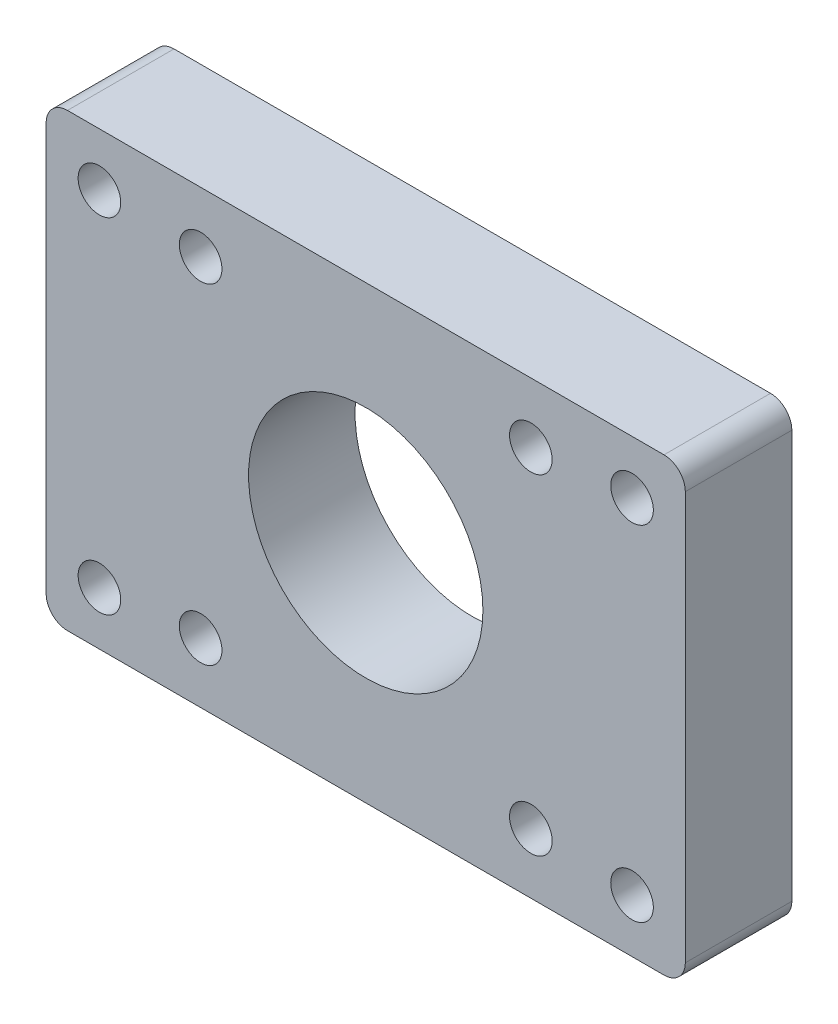
SolidWorks part; units mm, degrees
ref_plane "Plan de face" through (0, 0, 0) normal (0, 0, 1) x (1, 0, 0)
ref_plane "Plan de dessus" through (0, 0, 0) normal (0, 1, 0) x (1, 0, 0)
ref_plane "Plan de droite" through (0, 0, 0) normal (1, 0, 0) x (0, 0, -1)
sketch "Esquisse1" plane through (0, 0, 0) normal (0, 0, 1) x (1, 0, 0)
  line L0 (0, 0) -> (0, 40.0403) construction
  line L1 (-30, -21.15) -> (30, -21.15)
  line L2 (-30, -21.15) -> (-30, 21.15)
  line L3 (-30, 21.15) -> (30, 21.15)
  line L4 (30, -21.15) -> (30, 21.15)
  line L5 (-30, -21.15) -> (30, 21.15) construction
  line L6 (-30, 21.15) -> (30, -21.15) construction
  line L7 (0, 0) -> (80.9815, 0) construction
  circle A0 centre (15.5, 15.5) radius 2
  circle A1 centre (-15.5, 15.5) radius 2
  circle A2 centre (15.5, -15.5) radius 2
  circle A3 centre (-15.5, -15.5) radius 2
  circle A4 centre (25, 16.15) radius 2
  circle A5 centre (-25, 16.15) radius 2
  circle A6 centre (-25, -16.15) radius 2
  circle A7 centre (25, -16.15) radius 2
  point P0 (0, 0)
  point P19 (25.7097, 16.519)
  dimension "D3" = 15.5
  dimension "D4" = 15.5
  dimension "D5" = 4
  dimension "D6" = 5
  dimension "D7" = 5
  dimension "D8" = 4
  dimension "D1" = 60
  dimension "D2" = 42.3
extrude "Boss.-Extru.1" add sketch "Esquisse1" along normal blind 10
sketch "Esquisse2" plane through (0, 0, 10) normal (0, 0, 1) x (1, 0, 0)
  circle A0 centre (0, 0) radius 11
  dimension "D1" = 22
extrude "Enlèv. mat.-Extru.1" cut sketch "Esquisse2" against normal blind 10
fillet "Congé1" radius 2 4 edges at (-30, -21.15, 5) (30, -21.15, 5) (-30, 21.15, 5) (30, 21.15, 5)
